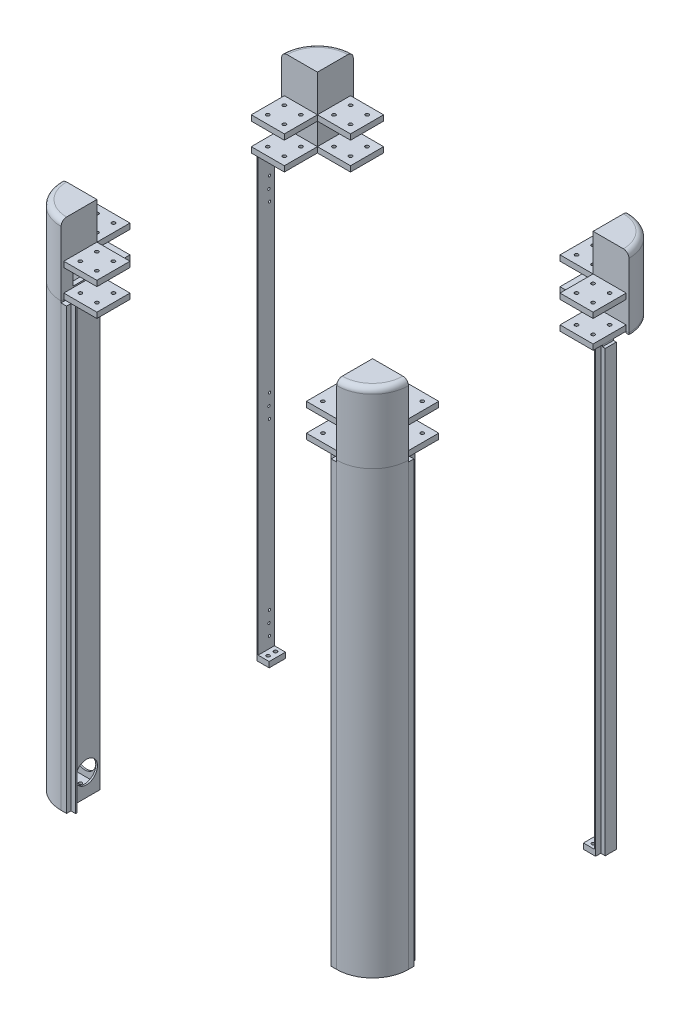
SolidWorks part; units mm, degrees
other "标注1"
sketch "草图29" plane through (-331.8736, 100, 281.3621) normal (-0.8506, -0.1647, 0.4994) x (0.4045, 0.4019, 0.8215)
material "锻制不锈钢"
ref_plane "前视基准面" through (0, 0, 0) normal (0, 0, 1) x (1, 0, 0)
ref_plane "上视基准面" through (0, 0, 0) normal (0, 1, 0) x (1, 0, 0)
ref_plane "右视基准面" through (0, 0, 0) normal (1, 0, 0) x (0, 0, -1)
other "Configuration Table"
sketch "草图1" plane through (0, 0, 0) normal (0, 1, 0) x (1, 0, 0)
  line L0 (298.1264, -216.3621) -> (233.1264, -216.3621)
  line L1 (233.1264, -216.3621) -> (233.1264, -281.3621)
  line L2 (-331.8736, -16.3621) -> (339.7931, -16.3621) construction
  line L3 (-16.8736, 278.315) -> (-16.8736, -277.7058) construction
  line L4 (233.1264, 183.6379) -> (233.1264, 248.6379)
  line L5 (298.1264, 183.6379) -> (233.1264, 183.6379)
  line L6 (-266.8736, -216.3621) -> (-266.8736, -281.3621)
  line L7 (-331.8736, -216.3621) -> (-266.8736, -216.3621)
  line L8 (-331.8736, 183.6379) -> (-266.8736, 183.6379)
  line L9 (-266.8736, 183.6379) -> (-266.8736, 248.6379)
  line L10 (-323.3137, 188.6379) -> (-271.8736, 188.6379)
  line L11 (-271.8736, 188.6379) -> (-271.8736, 240.0781)
  line L12 (289.5666, 188.6379) -> (238.1264, 188.6379)
  line L13 (238.1264, 188.6379) -> (238.1264, 240.0781)
  line L14 (238.1264, -221.3621) -> (238.1264, -272.8022)
  line L15 (289.5666, -221.3621) -> (238.1264, -221.3621)
  line L16 (-323.3137, -221.3621) -> (-271.8736, -221.3621)
  line L17 (-271.8736, -221.3621) -> (-271.8736, -272.8022)
  arc A0 (233.1264, -281.3621) -> (298.1264, -216.3621) centre (233.1264, -216.3621) ccw
  arc A1 (233.1264, 248.6379) -> (298.1264, 183.6379) centre (233.1264, 183.6379) cw
  arc A2 (-266.8736, -281.3621) -> (-331.8736, -216.3621) centre (-266.8736, -216.3621) cw
  arc A3 (-266.8736, 248.6379) -> (-331.8736, 183.6379) centre (-266.8736, 183.6379) ccw
  arc A4 (-271.8736, 240.0781) -> (-323.3137, 188.6379) centre (-271.8736, 188.6379) ccw
  arc A5 (238.1264, 240.0781) -> (289.5666, 188.6379) centre (238.1264, 188.6379) cw
  arc A6 (238.1264, -272.8022) -> (289.5666, -221.3621) centre (238.1264, -221.3621) ccw
  arc A7 (-271.8736, -272.8022) -> (-323.3137, -221.3621) centre (-271.8736, -221.3621) cw
  dimension "D1" = 65
  dimension "D2" = 500
  dimension "D3" = 400
  dimension "D4" = 5
  dimension "D5" = 5
extrude "凸台-拉伸1" add sketch "草图1" along normal blind 127 from offset 900 contours A7 L17 L16 | A2 L6 L7 L17 A7 L16 | L14 A6 L15 | L1 A0 L0 A6 L14 L15 | A5 L13 L12 | A1 L4 L5 L13 A5 L12 | L9 A3 L8 A4 L11 L10 | L11 A4 L10
sketch "草图5" plane through (0, 900, 0) normal (0, 1, 0) x (1, 0, 0)
  line L0 (-16.8736, 183.6379) -> (-16.8736, -216.3621) construction
  line L1 (-326.8736, 183.6379) -> (-266.8736, 183.6379)
  line L2 (-326.8736, 183.6379) -> (-326.8736, 123.6379)
  line L3 (-326.8736, 123.6379) -> (-266.8736, 123.6379)
  line L4 (-266.8736, 183.6379) -> (-266.8736, 123.6379)
  line L5 (-266.8736, 243.6379) -> (-206.8736, 243.6379)
  line L6 (-266.8736, 243.6379) -> (-266.8736, 183.6379)
  line L7 (-266.8736, 183.6379) -> (-206.8736, 183.6379)
  line L8 (-206.8736, 243.6379) -> (-206.8736, 183.6379)
  line L9 (-326.8736, 183.6379) -> (293.1264, 183.6379) construction
  line L10 (-326.8736, 183.6379) -> (-326.8736, -216.3621) construction
  line L11 (-326.8736, -216.3621) -> (293.1264, -216.3621) construction
  line L12 (293.1264, 183.6379) -> (293.1264, -216.3621) construction
  line L13 (-326.8736, -16.3621) -> (293.1264, -16.3621) construction
  line L14 (-326.8736, -156.3621) -> (-266.8736, -156.3621)
  line L15 (-266.8736, -216.3621) -> (-266.8736, -156.3621)
  line L16 (-326.8736, -216.3621) -> (-266.8736, -216.3621)
  line L17 (-326.8736, -216.3621) -> (-326.8736, -156.3621)
  line L18 (-266.8736, -216.3621) -> (-206.8736, -216.3621)
  line L19 (-206.8736, -276.3621) -> (-206.8736, -216.3621)
  line L20 (-266.8736, -276.3621) -> (-206.8736, -276.3621)
  line L21 (-266.8736, -276.3621) -> (-266.8736, -216.3621)
  line L22 (233.1264, -276.3621) -> (233.1264, -216.3621)
  line L23 (233.1264, -276.3621) -> (173.1264, -276.3621)
  line L24 (173.1264, -276.3621) -> (173.1264, -216.3621)
  line L25 (233.1264, -216.3621) -> (173.1264, -216.3621)
  line L26 (233.1264, -216.3621) -> (233.1264, -156.3621)
  line L27 (293.1264, -156.3621) -> (233.1264, -156.3621)
  line L28 (293.1264, -216.3621) -> (293.1264, -156.3621)
  line L29 (293.1264, -216.3621) -> (233.1264, -216.3621)
  line L30 (233.1264, 183.6379) -> (173.1264, 183.6379)
  line L31 (173.1264, 243.6379) -> (173.1264, 183.6379)
  line L32 (233.1264, 243.6379) -> (173.1264, 243.6379)
  line L33 (233.1264, 243.6379) -> (233.1264, 183.6379)
  line L34 (293.1264, 123.6379) -> (233.1264, 123.6379)
  line L35 (233.1264, 183.6379) -> (233.1264, 123.6379)
  line L36 (293.1264, 183.6379) -> (233.1264, 183.6379)
  line L37 (293.1264, 183.6379) -> (293.1264, 123.6379)
  line L38 (-266.8736, 183.6379) -> (-312.8355, 229.5999) construction
  circle A1 centre (-251.8736, 228.6379) radius 3.1
  circle A2 centre (-221.8736, 228.6379) radius 3.1
  circle A3 centre (-251.8736, 198.6379) radius 3.1
  circle A4 centre (-221.8736, 198.6379) radius 3.1
  circle A5 centre (-281.8736, 168.6379) radius 3.1
  circle A6 centre (-281.8736, 138.6379) radius 3.1
  circle A7 centre (-311.8736, 138.6379) radius 3.1
  circle A8 centre (-311.8736, 168.6379) radius 3.1
  circle A9 centre (-281.8736, -171.3621) radius 3.1
  circle A10 centre (-311.8736, -171.3621) radius 3.1
  circle A11 centre (-311.8736, -201.3621) radius 3.1
  circle A12 centre (-281.8736, -201.3621) radius 3.1
  circle A13 centre (-251.8736, -231.3621) radius 3.1
  circle A14 centre (-221.8736, -231.3621) radius 3.1
  circle A15 centre (-221.8736, -261.3621) radius 3.1
  circle A16 centre (-251.8736, -261.3621) radius 3.1
  circle A17 centre (218.1264, -261.3621) radius 3.1
  circle A18 centre (188.1264, -261.3621) radius 3.1
  circle A19 centre (188.1264, -231.3621) radius 3.1
  circle A20 centre (218.1264, -231.3621) radius 3.1
  circle A21 centre (248.1264, -201.3621) radius 3.1
  circle A22 centre (278.1264, -201.3621) radius 3.1
  circle A23 centre (278.1264, -171.3621) radius 3.1
  circle A24 centre (248.1264, -171.3621) radius 3.1
  circle A25 centre (278.1264, 168.6379) radius 3.1
  circle A26 centre (278.1264, 138.6379) radius 3.1
  circle A27 centre (248.1264, 138.6379) radius 3.1
  circle A28 centre (248.1264, 168.6379) radius 3.1
  circle A29 centre (188.1264, 198.6379) radius 3.1
  circle A30 centre (218.1264, 198.6379) radius 3.1
  circle A31 centre (188.1264, 228.6379) radius 3.1
  circle A32 centre (218.1264, 228.6379) radius 3.1
  dimension "D1" = 60
  dimension "D2" = 60
  dimension "D3" = 30
  dimension "D4" = 15
  dimension "D5" = 15
  dimension "D6" = 30
  dimension "D7" = 60
  dimension "D8" = 60
extrude "凸台-拉伸2" add sketch "草图5" along normal blind 10 from offset 50 separate body
sketch "草图7" plane through (0, 900, 0) normal (0, 1, 0) x (1, 0, 0)
  line L0 (-16.8736, 183.6379) -> (-16.8736, -216.3621) construction
  line L1 (-326.8736, 183.6379) -> (-266.8736, 183.6379)
  line L2 (-326.8736, 183.6379) -> (-326.8736, 123.6379)
  line L3 (-326.8736, 123.6379) -> (-266.8736, 123.6379)
  line L4 (-266.8736, 183.6379) -> (-266.8736, 123.6379)
  line L5 (-266.8736, 243.6379) -> (-206.8736, 243.6379)
  line L6 (-266.8736, 243.6379) -> (-266.8736, 183.6379)
  line L7 (-266.8736, 183.6379) -> (-206.8736, 183.6379)
  line L8 (-206.8736, 243.6379) -> (-206.8736, 183.6379)
  line L9 (-326.8736, 183.6379) -> (293.1264, 183.6379) construction
  line L10 (-326.8736, 183.6379) -> (-326.8736, -216.3621) construction
  line L11 (-326.8736, -216.3621) -> (293.1264, -216.3621) construction
  line L12 (293.1264, 183.6379) -> (293.1264, -216.3621) construction
  line L13 (-326.8736, -16.3621) -> (293.1264, -16.3621) construction
  line L14 (-326.8736, -156.3621) -> (-266.8736, -156.3621)
  line L15 (-266.8736, -216.3621) -> (-266.8736, -156.3621)
  line L16 (-326.8736, -216.3621) -> (-266.8736, -216.3621)
  line L17 (-326.8736, -216.3621) -> (-326.8736, -156.3621)
  line L18 (-266.8736, -216.3621) -> (-206.8736, -216.3621)
  line L19 (-206.8736, -276.3621) -> (-206.8736, -216.3621)
  line L20 (-266.8736, -276.3621) -> (-206.8736, -276.3621)
  line L21 (-266.8736, -276.3621) -> (-266.8736, -216.3621)
  line L22 (233.1264, -276.3621) -> (233.1264, -216.3621)
  line L23 (233.1264, -276.3621) -> (173.1264, -276.3621)
  line L24 (173.1264, -276.3621) -> (173.1264, -216.3621)
  line L25 (233.1264, -216.3621) -> (173.1264, -216.3621)
  line L26 (233.1264, -216.3621) -> (233.1264, -156.3621)
  line L27 (293.1264, -156.3621) -> (233.1264, -156.3621)
  line L28 (293.1264, -216.3621) -> (293.1264, -156.3621)
  line L29 (293.1264, -216.3621) -> (233.1264, -216.3621)
  line L30 (233.1264, 183.6379) -> (173.1264, 183.6379)
  line L31 (173.1264, 243.6379) -> (173.1264, 183.6379)
  line L32 (233.1264, 243.6379) -> (173.1264, 243.6379)
  line L33 (233.1264, 243.6379) -> (233.1264, 183.6379)
  line L34 (293.1264, 123.6379) -> (233.1264, 123.6379)
  line L35 (233.1264, 183.6379) -> (233.1264, 123.6379)
  line L36 (293.1264, 183.6379) -> (233.1264, 183.6379)
  line L37 (293.1264, 183.6379) -> (293.1264, 123.6379)
  line L38 (-266.8736, 183.6379) -> (-339.378, 256.1424) construction
  circle A0 centre (-251.8736, 228.6379) radius 3.1
  circle A1 centre (-221.8736, 228.6379) radius 3.1
  circle A2 centre (-251.8736, 198.6379) radius 3.1
  circle A3 centre (-221.8736, 198.6379) radius 3.1
  circle A4 centre (-281.8736, 168.6379) radius 3.1
  circle A5 centre (-281.8736, 138.6379) radius 3.1
  circle A6 centre (-311.8736, 138.6379) radius 3.1
  circle A7 centre (-311.8736, 168.6379) radius 3.1
  circle A8 centre (-281.8736, -171.3621) radius 3.1
  circle A9 centre (-311.8736, -171.3621) radius 3.1
  circle A10 centre (-311.8736, -201.3621) radius 3.1
  circle A11 centre (-281.8736, -201.3621) radius 3.1
  circle A12 centre (-251.8736, -231.3621) radius 3.1
  circle A13 centre (-221.8736, -231.3621) radius 3.1
  circle A14 centre (-221.8736, -261.3621) radius 3.1
  circle A15 centre (-251.8736, -261.3621) radius 3.1
  circle A16 centre (218.1264, -261.3621) radius 3.1
  circle A17 centre (188.1264, -261.3621) radius 3.1
  circle A18 centre (188.1264, -231.3621) radius 3.1
  circle A19 centre (218.1264, -231.3621) radius 3.1
  circle A20 centre (248.1264, -201.3621) radius 3.1
  circle A21 centre (278.1264, -201.3621) radius 3.1
  circle A22 centre (278.1264, -171.3621) radius 3.1
  circle A23 centre (248.1264, -171.3621) radius 3.1
  circle A24 centre (278.1264, 168.6379) radius 3.1
  circle A25 centre (278.1264, 138.6379) radius 3.1
  circle A26 centre (248.1264, 138.6379) radius 3.1
  circle A27 centre (248.1264, 168.6379) radius 3.1
  circle A28 centre (188.1264, 198.6379) radius 3.1
  circle A29 centre (218.1264, 198.6379) radius 3.1
  circle A30 centre (188.1264, 228.6379) radius 3.1
  circle A31 centre (218.1264, 228.6379) radius 3.1
  line M87 (298.1264, 183.6379) -> (233.1264, 183.6379)
  line M88 (233.1264, 183.6379) -> (233.1264, 248.6379)
  dimension "D1" = 60
  dimension "D2" = 60
  dimension "D3" = 30
  dimension "D4" = 15
  dimension "D5" = 15
  dimension "D6" = 30
  dimension "D7" = 60
  dimension "D8" = 60
extrude "凸台-拉伸3" add sketch "草图7" along normal blind 10 contours L32 L30 L31 A31 A30 A29 A28 M88 | L37 L34 L35 A26 A24 A25 A27 M87 | L5 L8 L7 L6 A2 A0 A1 A3 | L1 L4 L3 L2 A7 A6 A5 A4 | L16 L17 L14 L15 A10 A8 A9 A11 | L20 L21 L18 L19 A15 A14 A13 A12 | L28 L29 L26 L27 A23 A22 A21 A20 | L25 L22 L23 L24 A18 A16 A17 A19
sketch "草图13" plane through (0, 900, 0) normal (0, -1, 0) x (1, 0, 0)
  line L0 (-326.8736, 206.3621) -> (-323.8736, 206.3621)
  line L5 (-266.8736, 281.3621) -> (-256.8736, 281.3621)
  line L10 (-312.8355, 16.3621) -> (279.0884, 16.3621) construction
  line L11 (-312.8355, 262.324) -> (279.0884, 262.324) construction
  line L12 (-312.8355, 262.324) -> (-312.8355, -229.5999) construction
  line L13 (-312.8355, -229.5999) -> (279.0884, -229.5999) construction
  line L14 (279.0884, 262.324) -> (279.0884, -229.5999) construction
  line L15 (-16.8736, 262.324) -> (-16.8736, -229.5999) construction
  line L36 (-256.8736, 281.3621) -> (-256.8736, 276.3621)
  line L37 (-323.8736, 206.3621) -> (-323.8736, 196.0495)
  line L39 (-331.8736, 216.3621) -> (-331.8736, 206.3621)
  line L40 (-331.8736, 206.3621) -> (-326.8736, 206.3621)
  line L42 (-323.8736, 196.0495) -> (-321.8736, 196.0495)
  line L43 (-321.8736, 196.0495) -> (-321.8736, 216.3621)
  line L44 (-321.8736, 216.3621) -> (-326.8736, 216.3621)
  line L45 (-256.8736, 276.3621) -> (-256.8736, 273.3621)
  line L46 (-256.8736, 273.3621) -> (-248.3948, 273.3621)
  line L47 (-248.3948, 273.3621) -> (-248.3948, 271.3621)
  line L48 (-248.3948, 271.3621) -> (-266.8736, 271.3621)
  line L49 (-266.8736, 271.3621) -> (-266.8736, 276.3621)
  line L50 (233.1264, 271.3621) -> (233.1264, 276.3621)
  line L51 (214.6477, 271.3621) -> (233.1264, 271.3621)
  line L52 (214.6477, 273.3621) -> (214.6477, 271.3621)
  line L53 (223.1264, 273.3621) -> (214.6477, 273.3621)
  line L54 (223.1264, 276.3621) -> (223.1264, 273.3621)
  line L55 (288.1264, 216.3621) -> (293.1264, 216.3621)
  line L56 (288.1264, 196.0495) -> (288.1264, 216.3621)
  line L57 (290.1264, 196.0495) -> (288.1264, 196.0495)
  line L58 (298.1264, 206.3621) -> (293.1264, 206.3621)
  line L59 (298.1264, 216.3621) -> (298.1264, 206.3621)
  line L60 (290.1264, 206.3621) -> (290.1264, 196.0495)
  line L61 (223.1264, 281.3621) -> (223.1264, 276.3621)
  line L62 (233.1264, 281.3621) -> (223.1264, 281.3621)
  line L63 (293.1264, 206.3621) -> (290.1264, 206.3621)
  line L65 (233.1264, -248.6379) -> (223.1264, -248.6379)
  line L66 (223.1264, -248.6379) -> (223.1264, -243.6379)
  line L73 (223.1264, -243.6379) -> (223.1264, -240.6379)
  line L74 (223.1264, -240.6379) -> (214.6477, -240.6379)
  line L75 (214.6477, -240.6379) -> (214.6477, -238.6379)
  line L76 (214.6477, -238.6379) -> (233.1264, -238.6379)
  line L77 (233.1264, -238.6379) -> (233.1264, -243.6379)
  line L78 (-266.8736, -238.6379) -> (-266.8736, -243.6379)
  line L79 (-248.3948, -238.6379) -> (-266.8736, -238.6379)
  line L80 (-248.3948, -240.6379) -> (-248.3948, -238.6379)
  line L81 (-256.8736, -240.6379) -> (-248.3948, -240.6379)
  line L82 (-256.8736, -243.6379) -> (-256.8736, -240.6379)
  line L87 (-331.8736, -183.6379) -> (-331.8736, -160.6379)
  line L89 (-256.8736, -248.6379) -> (-256.8736, -243.6379)
  line L90 (-266.8736, -248.6379) -> (-256.8736, -248.6379)
  line L92 (-331.8736, -160.6379) -> (-331.8736, -140.6379)
  line L93 (-331.8736, -140.6379) -> (-323.8736, -140.6379)
  line L94 (-323.8736, -140.6379) -> (-323.8736, -131.0937)
  line L95 (-323.8736, -131.0937) -> (-321.8736, -131.0937)
  line L96 (-321.8736, -131.0937) -> (-321.8736, -160.6379)
  line L97 (-321.8736, -160.6379) -> (-326.8736, -160.6379)
  line L98 (-326.8736, -183.6379) -> (-326.8736, -160.6379)
  line L100 (293.1264, -183.6379) -> (293.1264, -160.6379)
  line L101 (298.1264, -183.6379) -> (298.1264, -160.6379)
  line L102 (288.1264, -160.6379) -> (293.1264, -160.6379)
  line L103 (288.1264, -131.0937) -> (288.1264, -160.6379)
  line L104 (290.1264, -131.0937) -> (288.1264, -131.0937)
  line L105 (290.1264, -140.6379) -> (290.1264, -131.0937)
  line L106 (298.1264, -140.6379) -> (290.1264, -140.6379)
  line L107 (298.1264, -160.6379) -> (298.1264, -140.6379)
  arc A3 (233.1264, -248.6379) -> (298.1264, -183.6379) centre (233.1264, -183.6379) ccw construction
  arc A14 (-266.8736, 276.3621) -> (-326.8736, 216.3621) centre (-266.8736, 216.3621) ccw
  arc A15 (-266.8736, 281.3621) -> (-331.8736, 216.3621) centre (-266.8736, 216.3621) ccw
  arc A19 (233.1264, 281.3621) -> (298.1264, 216.3621) centre (233.1264, 216.3621) cw
  arc A20 (233.1264, 276.3621) -> (293.1264, 216.3621) centre (233.1264, 216.3621) cw
  arc A21 (233.1264, -243.6379) -> (293.1264, -183.6379) centre (233.1264, -183.6379) ccw
  arc A22 (233.1264, -248.6379) -> (298.1264, -183.6379) centre (233.1264, -183.6379) ccw
  arc A23 (-266.8736, -248.6379) -> (-331.8736, -183.6379) centre (-266.8736, -183.6379) cw
  arc A24 (-266.8736, -243.6379) -> (-326.8736, -183.6379) centre (-266.8736, -183.6379) cw
  dimension "D1" = 10
  dimension "D2" = 10
  dimension "D3" = 8
  dimension "D4" = 2
  dimension "D5" = 8
  dimension "D6" = 2
  dimension "D7" = 8
  dimension "D8" = 2
  dimension "D9" = 23
  dimension "D10" = 20
extrude "凸台-拉伸9" add sketch "草图13" along normal blind 800 separate body
sketch "草图15" plane through (0, 0, 281.3621) normal (0, 0, 1) x (1, 0, 0)
  line L1 (-266.8736, 900) -> (-246.1592, 900)
  line L2 (-266.8736, 900) -> (-266.8736, 897)
  line L3 (-266.8736, 897) -> (-246.1592, 897)
  line L4 (-246.1592, 900) -> (-246.1592, 897)
  line L6 (210.5447, 900) -> (233.1264, 900)
  line L7 (210.5447, 900) -> (210.5447, 897)
  line L8 (210.5447, 897) -> (233.1264, 897)
  line L9 (233.1264, 900) -> (233.1264, 897)
  dimension "D1" = 3
  dimension "D2" = 3
extrude "切除-拉伸1" cut sketch "草图15" against normal through all
sketch "草图18" plane through (-331.8736, 0, 0) normal (-1, 0, 0) x (0, 0, 1)
  line L0 (-183.6379, 100) -> (-183.6379, 900) construction
  line L1 (-183.6379, 900) -> (-160.6379, 900)
  line L2 (-183.6379, 900) -> (-183.6379, 897)
  line L3 (-183.6379, 897) -> (-160.6379, 897)
  line L4 (-160.6379, 900) -> (-160.6379, 897)
  line L5 (216.3621, 100) -> (216.3621, 900) construction
  line L6 (195.3621, 900) -> (216.3621, 900)
  line L7 (195.3621, 900) -> (195.3621, 897)
  line L8 (195.3621, 897) -> (216.3621, 897)
  line L9 (216.3621, 900) -> (216.3621, 897)
  dimension "D1" = 3
  dimension "D2" = 3
  dimension "D3" = 23
  dimension "D4" = 21
extrude "切除-拉伸2" cut sketch "草图18" against normal through all
fillet "圆角1" radius 10 1 edges at (-312.8355, 1027, 262.324)
fillet "圆角2" radius 10 1 edges at (-312.8355, 1027, -229.5999)
fillet "圆角3" radius 10 1 edges at (279.0884, 1027, -229.5999)
fillet "圆角4" radius 10 1 edges at (279.0884, 1027, 262.324)
sketch "草图21" plane through (0, 0, -160.6379) normal (0, 0, -1) x (-1, 0, 0)
  line L0 (321.8736, 100) -> (321.8736, 900) construction
  line L1 (266.8736, 100) -> (331.8736, 100) construction
  circle A0 centre (336.8736, 130) radius 3
  circle A1 centre (336.8736, 157) radius 3
  dimension "D1" = 6
  dimension "D3" = 27
  dimension "D2" = 15
  dimension "D4" = 30
sketch "草图22" plane through (0, 100, 0) normal (0, -1, 0) x (1, 0, 0)
  line L0 (-326.8736, -160.6379) -> (-321.8736, -160.6379) construction
  line L1 (-349.6203, -160.6379) -> (316.2119, -160.6379)
  line L2 (-349.6203, -160.6379) -> (-349.6203, -278.3574)
  line L3 (-349.6203, -278.3574) -> (316.2119, -278.3574)
  line L4 (316.2119, -160.6379) -> (316.2119, -278.3574)
extrude "切除-拉伸7" cut sketch "草图22" against normal blind 797
sketch "草图23" plane through (-331.8736, 0, 0) normal (-1, 0, 0) x (0, 0, 1)
  line L0 (-140.6379, 100) -> (-160.6379, 100) construction
  line L1 (-140.6379, 100) -> (-140.6379, 900) construction
  line L2 (-140.6379, 500) -> (216.3621, 498.5) construction
  line L3 (-140.6379, 100) -> (-140.6379, 900) construction
  line L4 (216.3621, 100) -> (216.3621, 897) construction
  circle A0 centre (-151.6379, 130) radius 2.15
  circle A1 centre (-150.6379, 150.5) radius 2.15
  circle A2 centre (-151.6379, 171) radius 2.15
  circle A3 centre (-151.6379, 812) radius 2.15
  circle A4 centre (-150.6379, 832.5) radius 2.15
  circle A5 centre (-151.6379, 853) radius 2.15
  circle A6 centre (-151.6379, 471) radius 2.15
  circle A7 centre (-150.6379, 491.5) radius 2.15
  circle A8 centre (-151.6379, 512) radius 2.15
  dimension "D1" = 4.3
  dimension "D2" = 4.3
  dimension "D5" = 4.3
  dimension "D9" = 4.3
  dimension "D10" = 4.3
  dimension "D11" = 4.3
  dimension "D3" = 30
  dimension "D4" = 20.5
  dimension "D6" = 10
  dimension "D7" = 11
  dimension "D8" = 20.5
  dimension "D12" = 20.5
  dimension "D13" = 20.5
  dimension "D14" = 11
  dimension "D15" = 10
  dimension "D16" = 300
  dimension "D17" = 300
  dimension "D18" = 20.5
  dimension "D19" = 20.5
  dimension "D20" = 11
  dimension "D21" = 10
extrude "切除-拉伸8" cut sketch "草图23" against normal blind 10
sketch "草图24" plane through (0, 100, 0) normal (0, -1, 0) x (1, 0, 0)
  line L0 (-326.8736, 216.3621) -> (-266.8736, 216.3621)
  line L1 (-321.8736, -160.6379) -> (-301.8736, -160.6379)
  line L2 (-321.8736, -160.6379) -> (-321.8736, -131.0937)
  line L3 (-321.8736, -131.0937) -> (-301.8736, -131.0937)
  line L4 (-301.8736, -160.6379) -> (-301.8736, -131.0937)
  line L5 (-266.8736, 216.3621) -> (-266.8736, 276.3621)
  line L6 (-16.8736, 271.3621) -> (-16.8736, 216.3621) construction
  line L7 (-266.8736, 271.3621) -> (233.1264, 271.3621) construction
  line L8 (-266.8736, 271.3621) -> (-266.8736, 216.3621) construction
  line L9 (-266.8736, 216.3621) -> (233.1264, 216.3621) construction
  line L13 (-321.8736, -131.0937) -> (-323.8736, -131.0937) construction
  line L14 (268.1264, -160.6379) -> (268.1264, -131.0937)
  line L15 (288.1264, -131.0937) -> (268.1264, -131.0937)
  line L16 (288.1264, -160.6379) -> (288.1264, -131.0937)
  line L17 (288.1264, -160.6379) -> (268.1264, -160.6379)
  line L18 (233.1264, 271.3621) -> (233.1264, 216.3621) construction
  line L19 (233.1264, 216.3621) -> (233.1264, 276.3621)
  line L20 (293.1264, 216.3621) -> (233.1264, 216.3621)
  circle A0 centre (278.1264, -139.0937) radius 3
  arc A1 (-266.8736, 276.3621) -> (-326.8736, 216.3621) centre (-266.8736, 216.3621) ccw
  circle A4 centre (-311.8736, -152.6379) radius 3
  circle A5 centre (-311.8736, -139.0937) radius 3
  circle A6 centre (278.1264, -152.6379) radius 3
  circle A7 centre (-311.8736, 231.3621) radius 3
  circle A8 centre (-281.8736, 231.3621) radius 3
  circle A9 centre (-281.8736, 261.477) radius 3
  circle A10 centre (248.1264, 261.477) radius 3
  circle A11 centre (248.1264, 231.3621) radius 3
  circle A12 centre (278.1264, 231.3621) radius 3
  arc A13 (233.1264, 276.3621) -> (293.1264, 216.3621) centre (233.1264, 216.3621) cw
  dimension "D2" = 6
  dimension "D3" = 6
  dimension "D7" = 6
  dimension "D8" = 6
  dimension "D9" = 6
  dimension "D1" = 20
  dimension "D4" = 8
  dimension "D5" = 8
  dimension "D6" = 10
  dimension "D10" = 15
  dimension "D11" = 15
extrude "凸台-拉伸10" add sketch "草图24" against normal blind 10
sketch "草图25" plane through (0, 900, 0) normal (0, -1, 0) x (1, 0, 0)
  line L0 (-16.8736, 216.3621) -> (-16.8736, -183.6379) construction
  line L1 (-266.8736, 216.3621) -> (233.1264, 216.3621) construction
  line L2 (-266.8736, 216.3621) -> (-266.8736, -183.6379) construction
  line L3 (-266.8736, -183.6379) -> (233.1264, -183.6379) construction
  line L4 (233.1264, 216.3621) -> (233.1264, -183.6379) construction
  line L5 (-266.8736, 16.3621) -> (233.1264, 16.3621) construction
  line L6 (-321.8736, 216.3621) -> (-266.8736, 216.3621) construction
  line L7 (-309.8736, 224.3621) -> (-274.8736, 224.3621)
  line L8 (-309.8736, 224.3621) -> (-309.8736, 259.3621)
  line L9 (-309.8736, 259.3621) -> (-274.8736, 259.3621)
  line L10 (-274.8736, 224.3621) -> (-274.8736, 259.3621)
  line L11 (-309.8736, 224.3621) -> (-274.8736, 259.3621) construction
  line L12 (-309.8736, 259.3621) -> (-274.8736, 224.3621) construction
  line L13 (-266.8736, 216.3621) -> (-266.8736, 271.3621) construction
  line L14 (276.1264, 259.3621) -> (241.1264, 224.3621) construction
  line L15 (276.1264, 224.3621) -> (241.1264, 259.3621) construction
  line L16 (241.1264, 224.3621) -> (241.1264, 259.3621)
  line L17 (276.1264, 259.3621) -> (241.1264, 259.3621)
  line L18 (276.1264, 224.3621) -> (276.1264, 259.3621)
  line L19 (276.1264, 224.3621) -> (241.1264, 224.3621)
  dimension "D1" = 35
  dimension "D2" = 35
  dimension "D3" = 8
  dimension "D4" = 8
sketch "草图26" plane through (0, 100, 0) normal (0, -1, 0) x (1, 0, 0)
  line L0 (-266.8736, 216.3621) -> (-266.8736, -183.6379) construction
  line L1 (-321.8736, 216.3621) -> (-266.8736, 216.3621)
  line L2 (-321.8736, 216.3621) -> (-321.8736, 213.3621)
  line L3 (-321.8736, 213.3621) -> (-266.8736, 213.3621)
  line L5 (-266.8736, 16.3621) -> (233.1264, 16.3621) construction
  line L6 (-266.8736, 271.2903) -> (-263.8736, 271.2903)
  line L7 (-266.8736, 271.2903) -> (-266.8736, 216.3621)
  line L8 (-266.8736, 213.3621) -> (-263.8736, 213.3621)
  line L9 (-263.8736, 271.2903) -> (-263.8736, 213.3621)
  line L10 (-266.8736, 216.3621) -> (233.1264, 216.3621) construction
  line L11 (-266.8736, 216.3621) -> (-266.8736, -183.6379) construction
  line L12 (-266.8736, -183.6379) -> (233.1264, -183.6379) construction
  line L13 (233.1264, 216.3621) -> (233.1264, -183.6379) construction
  line L14 (-16.8736, 216.3621) -> (-16.8736, -183.6379) construction
  line L15 (230.1264, 271.2903) -> (230.1264, 213.3621)
  line L16 (233.1264, 213.3621) -> (230.1264, 213.3621)
  line L17 (233.1264, 271.2903) -> (233.1264, 216.3621)
  line L18 (233.1264, 271.2903) -> (230.1264, 271.2903)
  line L19 (288.1264, 213.3621) -> (233.1264, 213.3621)
  line L20 (288.1264, 216.3621) -> (288.1264, 213.3621)
  line L21 (288.1264, 216.3621) -> (233.1264, 216.3621)
  dimension "D1" = 3
  dimension "D2" = 3
extrude "凸台-拉伸11" add sketch "草图26" against normal blind 797 separate body
extrude "切除-拉伸9" cut sketch "草图25" against normal blind 45
sketch "草图27" plane through (0, 0, 216.3621) normal (0, 0, -1) x (-1, 0, 0)
  line L0 (-241.1264, 947.4998) -> (-276.1264, 912.5002) construction
  line L1 (-241.1264, 912.5002) -> (-276.1264, 947.4998) construction
  line L2 (-233.1264, 950) -> (266.8736, 950) construction
  line L3 (266.8736, 1017) -> (266.8736, 900) construction
  line L4 (16.8736, 950) -> (16.8736, 984.5625) construction
  line L5 (266.8736, 910) -> (206.8736, 910) construction
  line L6 (274.8736, 912.5002) -> (309.8736, 912.5002)
  line L7 (274.8736, 912.5002) -> (274.8736, 947.4998)
  line L8 (274.8736, 947.4998) -> (309.8736, 947.4998)
  line L9 (309.8736, 912.5002) -> (309.8736, 947.4998)
  line L10 (274.8736, 912.5002) -> (309.8736, 947.4998) construction
  line L11 (274.8736, 947.4998) -> (309.8736, 912.5002) construction
  line L12 (-276.1264, 912.5002) -> (-276.1264, 947.4998)
  line L13 (-241.1264, 947.4998) -> (-276.1264, 947.4998)
  line L14 (-241.1264, 912.5002) -> (-241.1264, 947.4998)
  line L15 (-241.1264, 912.5002) -> (-276.1264, 912.5002)
  dimension "D1" = 8
  dimension "D2" = 2.5002
  dimension "D4" = 35
  dimension "D5" = 34.9995
extrude "切除-拉伸10" cut sketch "草图27" against normal blind 40 contours L15 L14 L13 L12 | L6 L9 L8 L7
sketch "草图28" plane through (-266.8736, 0, 0) normal (1, 0, 0) x (0, 0, -1)
  line L2 (-216.3621, 1017) -> (-216.3621, 900) construction
  line L3 (-259.3621, 912.5) -> (-224.3621, 912.5)
  line L4 (-259.3621, 912.5) -> (-259.3621, 947.5)
  line L5 (-259.3621, 947.5) -> (-224.3621, 947.5)
  line L6 (-224.3621, 912.5) -> (-224.3621, 947.5)
  line L7 (-259.3621, 912.5) -> (-224.3621, 947.5) construction
  line L8 (-259.3621, 947.5) -> (-224.3621, 912.5) construction
  line L9 (-216.3621, 910) -> (-156.3621, 910) construction
  dimension "D2" = 2.5
  dimension "D1" = 8
  dimension "D4" = 35
  dimension "D5" = 35
extrude "切除-拉伸11" cut sketch "草图28" against normal blind 43 and the other way blind 543
sketch "草图30" plane through (0, 0, 213.3621) normal (0, 0, -1) x (-1, 0, 0)
  line L0 (263.8736, 897) -> (263.8736, 100) construction
  line L1 (321.8736, 100) -> (263.8736, 100) construction
  line L2 (-214.6477, 140) -> (248.3948, 140) construction
  line L3 (-214.6477, 100) -> (-214.6477, 897) construction
  line L4 (248.3948, 100) -> (248.3948, 897) construction
  line L5 (16.8736, 140) -> (16.8736, 173.2237) construction
  circle A0 centre (288.8736, 140) radius 20
  circle A1 centre (-255.1264, 140) radius 20
  dimension "D1" = 40
  dimension "D2" = 25
  dimension "D3" = 40
extrude "切除-拉伸12" cut sketch "草图30" against normal blind 10
sketch "草图31" plane through (230.1264, 0, 0) normal (-1, 0, 0) x (0, 0, 1)
  line L0 (271.2903, 100) -> (213.3621, 100) construction
  line L1 (213.3621, 897) -> (213.3621, 100) construction
  circle A0 centre (238.3621, 140) radius 20
  dimension "D1" = 40
  dimension "D2" = 40
  dimension "D3" = 25
extrude "切除-拉伸13" cut sketch "草图31" against normal blind 10 and the other way blind 509
sketch "草图32" plane through (0, 0, 216.3621) normal (0, 0, -1) x (-1, 0, 0)
  line L1 (-241.1264, 947.4998) -> (-233.1264, 947.4998)
  line L2 (-241.1264, 947.4998) -> (-241.1264, 912.5002)
  line L3 (-241.1264, 912.5002) -> (-233.1264, 912.5002)
  line L4 (-233.1264, 947.4998) -> (-233.1264, 912.5002)
  line L6 (-241.1264, 912.5002) -> (-276.1264, 912.5002) construction
  line L7 (-233.1264, 1027) -> (-233.1264, 910) construction
extrude "切除-拉伸14" cut sketch "草图32" against normal blind 10
sketch "草图33" plane through (0, 0, 216.3621) normal (0, 0, -1) x (-1, 0, 0)
  line L0 (274.8736, 912.5002) -> (309.8736, 912.5002) construction
  line L1 (274.8736, 947.4998) -> (266.8736, 947.4998)
  line L2 (274.8736, 947.4998) -> (274.8736, 912.5002)
  line L3 (274.8736, 912.5002) -> (266.8736, 912.5002)
  line L4 (266.8736, 947.4998) -> (266.8736, 912.5002)
  line L5 (266.8736, 1027) -> (266.8736, 910) construction
extrude "切除-拉伸15" cut sketch "草图33" against normal blind 10
sketch "草图34" plane through (-331.8736, 0, 0) normal (-1, 0, 0) x (0, 0, 1)
  line L0 (-140.6379, 100) -> (-140.6379, 900) construction
  line L1 (-160.6379, 900) -> (-140.6379, 900)
  line L2 (-160.6379, 900) -> (-160.6379, 897)
  line L3 (-160.6379, 897) -> (-140.6379, 897)
  line L4 (-140.6379, 900) -> (-140.6379, 897)
  dimension "D1" = 3
extrude "切除-拉伸16" cut sketch "草图34" against normal blind 5
sketch "草图35" plane through (298.1264, 0, 0) normal (1, 0, 0) x (0, 0, -1)
  line L0 (160.6379, 100) -> (160.6379, 900) construction
  line L1 (140.6379, 900) -> (160.6379, 900)
  line L2 (140.6379, 900) -> (140.6379, 897)
  line L3 (140.6379, 897) -> (160.6379, 897)
  line L4 (160.6379, 900) -> (160.6379, 897)
  dimension "D1" = 3
extrude "切除-拉伸17" cut sketch "草图35" against normal blind 5
